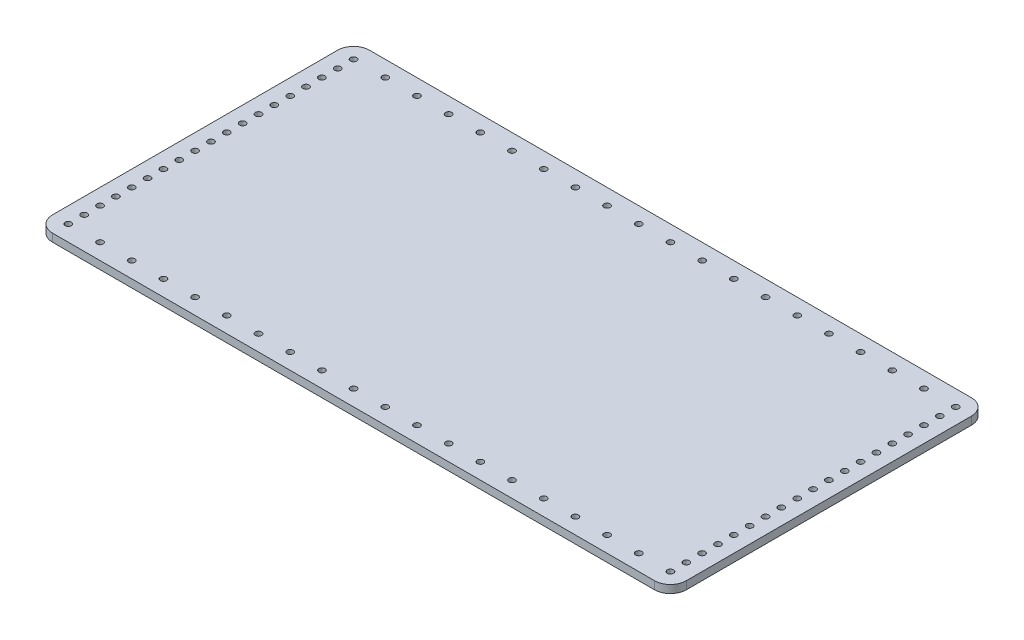
SolidWorks part; units mm, degrees
material "PC High Viscosity"
ref_plane "Front Plane" through (0, 0, 0) normal (0, 0, 1) x (1, 0, 0)
ref_plane "Top Plane" through (0, 0, 0) normal (0, 1, 0) x (1, 0, 0)
ref_plane "Right Plane" through (0, 0, 0) normal (1, 0, 0) x (0, 0, -1)
sketch "Sketch1" plane through (0, 0, 0) normal (0, 1, 0) x (1, 0, 0)
  line L1 (0, 0) -> (508, 0)
  line L2 (0, 0) -> (0, 254)
  line L3 (0, 254) -> (508, 254)
  line L4 (508, 0) -> (508, 254)
  dimension "D1" = 508
  dimension "D2" = 254
extrude "Boss-Extrude1" add sketch "Sketch1" along normal blind 6.35
sketch "Sketch3" plane through (0, 6.35, 0) normal (0, 1, 0) x (1, 0, 0)
  line L0 (508, 254) -> (0, 254) construction
  line L1 (0, 254) -> (0, 0) construction
  line L2 (12.7, 241.3) -> (38.1, 241.3) construction
  line L3 (12.7, 241.3) -> (12.7, 228.6) construction
  line L4 (12.7, 12.7) -> (38.1, 12.7) construction
  line L5 (12.7, 215.9) -> (12.7, 190.5) construction
  line L6 (495.3, 241.3) -> (495.3, 228.6) construction
  circle A0 centre (12.7, 241.3) radius 2.4892
  circle A1 centre (38.1, 241.3) radius 2.4892
  circle A2 centre (63.5, 241.3) radius 2.4892
  circle A3 centre (88.9, 241.3) radius 2.4892
  circle A4 centre (114.3, 241.3) radius 2.4892
  circle A5 centre (139.7, 241.3) radius 2.4892
  circle A6 centre (165.1, 241.3) radius 2.4892
  circle A7 centre (190.5, 241.3) radius 2.4892
  circle A8 centre (215.9, 241.3) radius 2.4892
  circle A9 centre (241.3, 241.3) radius 2.4892
  circle A10 centre (266.7, 241.3) radius 2.4892
  circle A11 centre (292.1, 241.3) radius 2.4892
  circle A12 centre (317.5, 241.3) radius 2.4892
  circle A13 centre (342.9, 241.3) radius 2.4892
  circle A14 centre (368.3, 241.3) radius 2.4892
  circle A15 centre (393.7, 241.3) radius 2.4892
  circle A16 centre (419.1, 241.3) radius 2.4892
  circle A17 centre (444.5, 241.3) radius 2.4892
  circle A18 centre (469.9, 241.3) radius 2.4892
  circle A19 centre (495.3, 241.3) radius 2.4892
  circle A23 centre (12.7, 228.6) radius 2.4892
  circle A24 centre (12.7, 215.9) radius 2.4892
  circle A25 centre (12.7, 203.2) radius 2.4892
  circle A26 centre (12.7, 190.5) radius 2.4892
  circle A27 centre (12.7, 177.8) radius 2.4892
  circle A28 centre (12.7, 165.1) radius 2.4892
  circle A29 centre (12.7, 152.4) radius 2.4892
  circle A30 centre (12.7, 139.7) radius 2.4892
  circle A31 centre (12.7, 127) radius 2.4892
  circle A32 centre (12.7, 114.3) radius 2.4892
  circle A33 centre (12.7, 101.6) radius 2.4892
  circle A56 centre (12.7, 215.9) radius 2.4892
  circle A57 centre (12.7, 190.5) radius 2.4892
  circle A58 centre (12.7, 165.1) radius 2.4892
  circle A59 centre (12.7, 139.7) radius 2.4892
  circle A60 centre (12.7, 114.3) radius 2.4892
  circle A61 centre (12.7, 88.9) radius 2.4892
  circle A62 centre (12.7, 63.5) radius 2.4892
  circle A63 centre (12.7, 38.1) radius 2.4892
  circle A64 centre (12.7, 12.7) radius 2.4892
  circle A65 centre (12.7, 88.9) radius 2.4892
  circle A66 centre (12.7, 76.2) radius 2.4892
  circle A67 centre (12.7, 63.5) radius 2.4892
  circle A68 centre (12.7, 50.8) radius 2.4892
  circle A69 centre (12.7, 38.1) radius 2.4892
  circle A70 centre (12.7, 25.4) radius 2.4892
  circle A71 centre (12.7, 12.7) radius 2.4892
  circle A72 centre (38.1, 12.7) radius 2.4892
  circle A73 centre (63.5, 12.7) radius 2.4892
  circle A74 centre (88.9, 12.7) radius 2.4892
  circle A75 centre (114.3, 12.7) radius 2.4892
  circle A76 centre (139.7, 12.7) radius 2.4892
  circle A77 centre (165.1, 12.7) radius 2.4892
  circle A78 centre (190.5, 12.7) radius 2.4892
  circle A79 centre (215.9, 12.7) radius 2.4892
  circle A80 centre (241.3, 12.7) radius 2.4892
  circle A81 centre (266.7, 12.7) radius 2.4892
  circle A82 centre (292.1, 12.7) radius 2.4892
  circle A83 centre (317.5, 12.7) radius 2.4892
  circle A84 centre (342.9, 12.7) radius 2.4892
  circle A85 centre (368.3, 12.7) radius 2.4892
  circle A86 centre (393.7, 12.7) radius 2.4892
  circle A87 centre (419.1, 12.7) radius 2.4892
  circle A88 centre (444.5, 12.7) radius 2.4892
  circle A89 centre (469.9, 12.7) radius 2.4892
  circle A90 centre (495.3, 12.7) radius 2.4892
  circle A91 centre (495.3, 228.6) radius 2.4892
  circle A92 centre (495.3, 215.9) radius 2.4892
  circle A93 centre (495.3, 203.2) radius 2.4892
  circle A94 centre (495.3, 190.5) radius 2.4892
  circle A95 centre (495.3, 177.8) radius 2.4892
  circle A96 centre (495.3, 165.1) radius 2.4892
  circle A97 centre (495.3, 152.4) radius 2.4892
  circle A98 centre (495.3, 139.7) radius 2.4892
  circle A99 centre (495.3, 127) radius 2.4892
  circle A100 centre (495.3, 114.3) radius 2.4892
  circle A101 centre (495.3, 101.6) radius 2.4892
  circle A102 centre (495.3, 88.9) radius 2.4892
  circle A103 centre (495.3, 76.2) radius 2.4892
  circle A104 centre (495.3, 63.5) radius 2.4892
  circle A105 centre (495.3, 50.8) radius 2.4892
  circle A106 centre (495.3, 38.1) radius 2.4892
  circle A107 centre (495.3, 25.4) radius 2.4892
  dimension "D1" = 12.7
  dimension "D2" = 4.9784
  dimension "D3" = 12.7
  dimension "D10" = 12.7
  dimension "D5" = 25.4
  dimension "D7" = 12.7
  dimension "D9" = 25.4
  dimension "D12" = 25.4
  dimension "D14" = 12.7
  dimension "D4" = 20
  dimension "D6" = 19
  dimension "D11" = 9
  dimension "D8" = 20
  dimension "D13" = 18
fillet "Fillet1" radius 12.7 4 edges at (508, 3.175, -254) (508, 3.175, 0) (0, 3.175, 0) (0, 3.175, -254)
extrude "Cut-Extrude2" cut sketch "Sketch3" against normal through all contours A25 | A24 | A23 | A0 | A1 | A2 | A3 | A4 | A64 | A70 | A63 | A68 | A62 | A72 | A73 | A74 | A33 | A32 | A31 | A30 | A28 | A29 | A27 | A26 | A61 | A66 | A90 | A89 | A88 | A87 | A86 | A85 | A84 | A83 | A82 | A81 | A80 | A79 | A75 | A76 | A77 | A78 | A5 | A6 | A7 | A8 | A9 | A10 | A11 | A12 | A13 | A14 | A15 | A16 | A17 | A18 | A19 | A107 | A106 | A105 | A101 | A102 | A103 | A104 | A100 | A99 | A98 | A97 | A96 | A95 | A94 | A93 | A91 | A92
